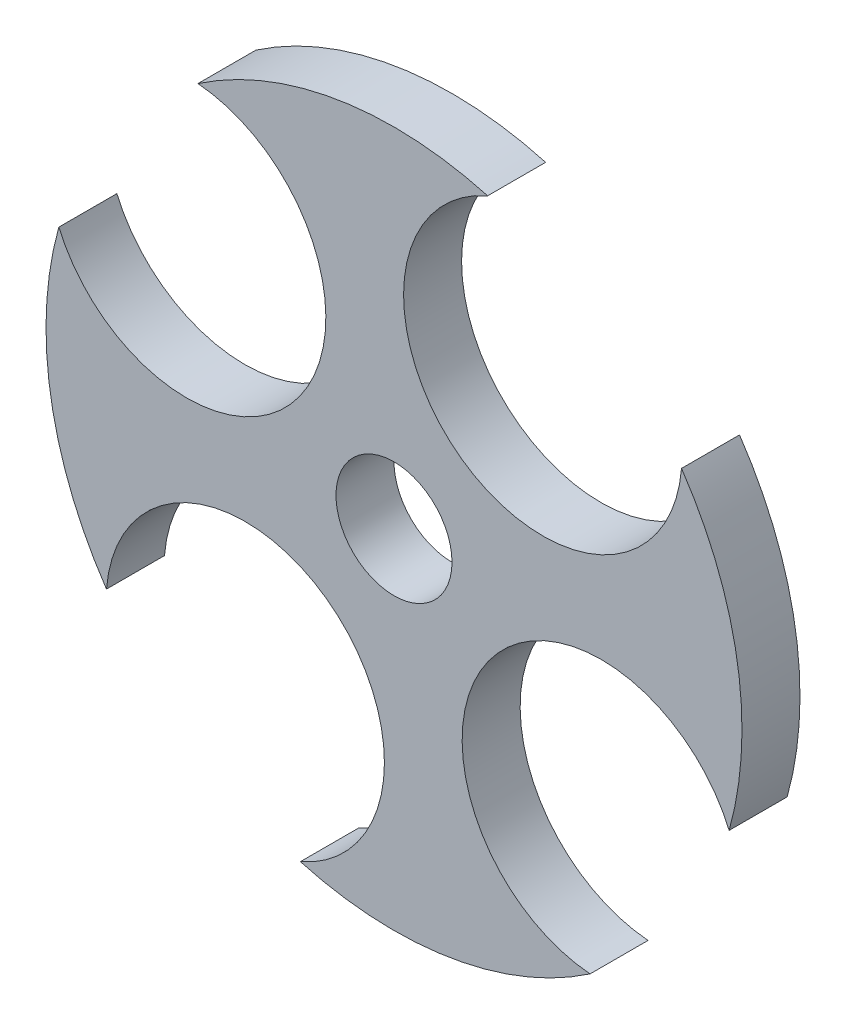
SolidWorks part; units mm, degrees
ref_plane "Front Plane" through (0, 0, 0) normal (0, 0, 1) x (1, 0, 0)
ref_plane "Top Plane" through (0, 0, 0) normal (0, 1, 0) x (1, 0, 0)
ref_plane "Right Plane" through (0, 0, 0) normal (1, 0, 0) x (0, 0, -1)
sketch "Sketch1" plane through (0, 0, 0) normal (0, 0, 1) x (1, 0, 0)
  arc A0 (-18.3471, 5.1269) -> (-15.7395, -10.7317) centre (0, 0) ccw
  circle A1 centre (0, 0) radius 3.175
  arc A2 (-18.3471, 5.1269) -> (-10.7317, 15.7395) centre (-11.3501, 8.1446) ccw
  arc A3 (5.1269, 18.3471) -> (15.7395, 10.7317) centre (8.1446, 11.3501) ccw
  arc A4 (18.3471, -5.1269) -> (10.7317, -15.7395) centre (11.3501, -8.1446) ccw
  arc A5 (-5.1269, -18.3471) -> (-15.7395, -10.7317) centre (-8.1446, -11.3501) ccw
  arc A6 (18.3471, -5.1269) -> (15.7395, 10.7317) centre (0, 0) ccw
  arc A7 (5.1269, 18.3471) -> (-10.7317, 15.7395) centre (0, 0) ccw
  arc A8 (-5.1269, -18.3471) -> (10.7317, -15.7395) centre (0, 0) ccw
  dimension "D1" = 38.1
  dimension "D3" = 6.35
  dimension "D4" = 15.24
  dimension "D6" = 15.24
  dimension "D7" = 15.24
  dimension "D8" = 15.24
extrude "Boss-Extrude1" add sketch "Sketch1" along normal blind 3.175
